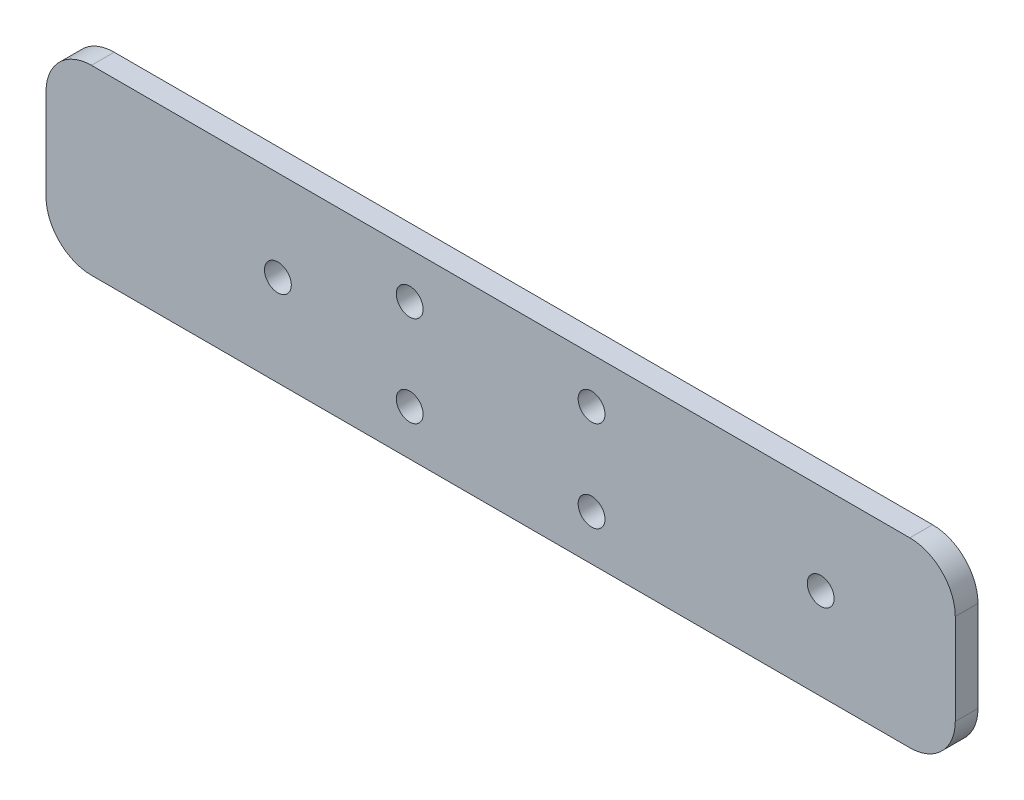
SolidWorks part; units mm, degrees
ref_plane "Alzado" through (0, 0, 0) normal (0, 0, 1) x (1, 0, 0)
ref_plane "Planta" through (0, 0, 0) normal (0, 1, 0) x (1, 0, 0)
ref_plane "Vista lateral" through (0, 0, 0) normal (1, 0, 0) x (0, 0, -1)
sketch "Croquis1" plane through (0, 0, 0) normal (0, 0, 1) x (1, 0, 0)
  line L0 (-25, -5) -> (162.963, -5) construction
  line L1 (-25, -5) -> (-25, 62.6248) construction
  line L2 (-125, -25) -> (-125, 15)
  line L3 (75, -25) -> (75, 15)
  line L4 (75, 15) -> (-125, 15)
  line L5 (75, -25) -> (-125, -25)
  dimension "D1" = 200
  dimension "D2" = 40
extrude "Extruir1" add sketch "Croquis1" along normal mid plane 5
fillet "Redondeo1" radius 10 4 edges at (-125, -25, 0) (75, -25, 0) (75, 15, 0) (-125, 15, 0)
sketch "Croquis2" plane through (0, 0, -2.5) normal (0, 0, -1) x (-1, 0, 0)
  circle A0 centre (73.9995, -4.903) radius 2.95 construction
  circle A1 centre (73.9995, -4.903) radius 2.95
extrude "Cortar-Extruir1" cut sketch "Croquis2" against normal blind 10
sketch "Croquis3" plane through (0, 0, 2.5) normal (0, 0, 1) x (1, 0, 0)
  circle A0 centre (-45, 5) radius 2.95 construction
  circle A1 centre (-45, 5) radius 2.95
  circle A2 centre (-5, 5) radius 2.95 construction
  circle A3 centre (-45, -15) radius 2.95 construction
  circle A4 centre (-5, -15) radius 2.95 construction
  circle A5 centre (-5, 5) radius 2.95
  circle A6 centre (-45, -15) radius 2.95
  circle A7 centre (-5, -15) radius 2.95
extrude "Cortar-Extruir2" cut sketch "Croquis3" against normal blind 10
sketch "Croquis4" plane through (0, 0, 2.5) normal (0, 0, 1) x (1, 0, 0)
  circle A0 centre (45.4005, -4.903) radius 2.95 construction
  circle A1 centre (45.4005, -4.903) radius 2.95
extrude "Cortar-Extruir3" cut sketch "Croquis4" against normal blind 10
